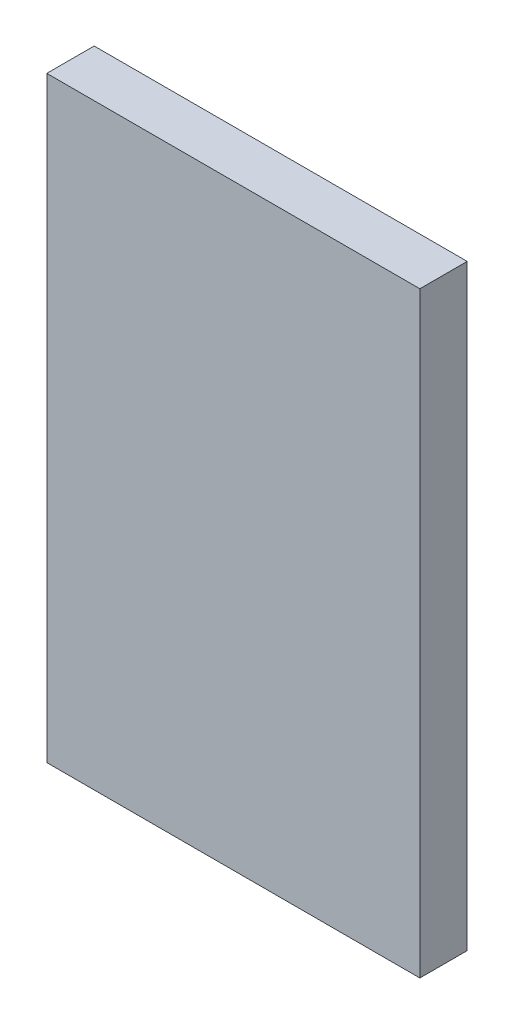
SolidWorks part; units mm, degrees
material "Acrylic (Medium-high impact)"
ref_plane "Front Plane" through (0, 0, 0) normal (0, 0, 1) x (1, 0, 0)
ref_plane "Top Plane" through (0, 0, 0) normal (0, 1, 0) x (1, 0, 0)
ref_plane "Right Plane" through (0, 0, 0) normal (1, 0, 0) x (0, 0, -1)
sketch "Sketch1" plane through (0, 0, 0) normal (0, 0, 1) x (1, 0, 0)
  line L1 (-25, -40) -> (25, -40)
  line L2 (-25, -40) -> (-25, 40)
  line L3 (-25, 40) -> (25, 40)
  line L4 (25, -40) -> (25, 40)
  line L5 (-25, -40) -> (25, 40) construction
  line L6 (-25, 40) -> (25, -40) construction
  point P0 (0, 0)
  dimension "D1" = 80
  dimension "D2" = 50
extrude "Boss-Extrude1" add sketch "Sketch1" along normal blind 6.35
